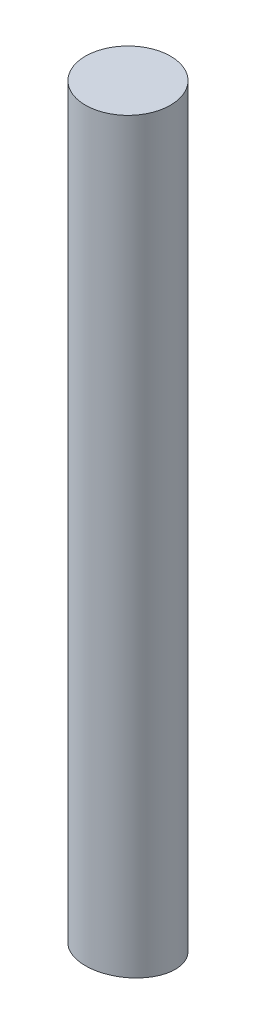
SolidWorks part; units mm, degrees
ref_plane "前视基准面" through (0, 0, 0) normal (0, 0, 1) x (1, 0, 0)
ref_plane "上视基准面" through (0, 0, 0) normal (0, 1, 0) x (1, 0, 0)
ref_plane "右视基准面" through (0, 0, 0) normal (1, 0, 0) x (0, 0, -1)
sketch "草图1" plane through (0, 0, 0) normal (0, -1, 0) x (1, 0, 0)
  circle A0 centre (-208, -27) radius 45
extrude "凸台-拉伸1" add sketch "草图1" along normal blind 800
sketch "草图2" plane through (0, -800, 0) normal (0, -1, 0) x (1, 0, 0)
  line L1 (-208, -72) -> (-163, -72) construction
  circle A1 centre (-208, -27) radius 45 construction
ref_plane "基准面1" through (0, -779.4091, 95.6994) normal (0, -0.9925, 0.1219) x (1, 0, 0)
sketch "草图3" plane through (0, -779.4091, 95.6994) normal (0, -0.9925, 0.1219) x (1, 0, 0)
  circle A0 centre (0, 0) radius 328.4954
extrude "切除-拉伸1" cut sketch "草图3" along normal blind 20
sketch "草图4" plane through (0, 0, 0) normal (0, 1, 0) x (1, 0, 0)
  line L0 (-208, 72) -> (-208, -9.606) construction
ref_plane "基准面2" through (-208, 0, 0) normal (-1, 0, 0) x (0, 0, 1)
